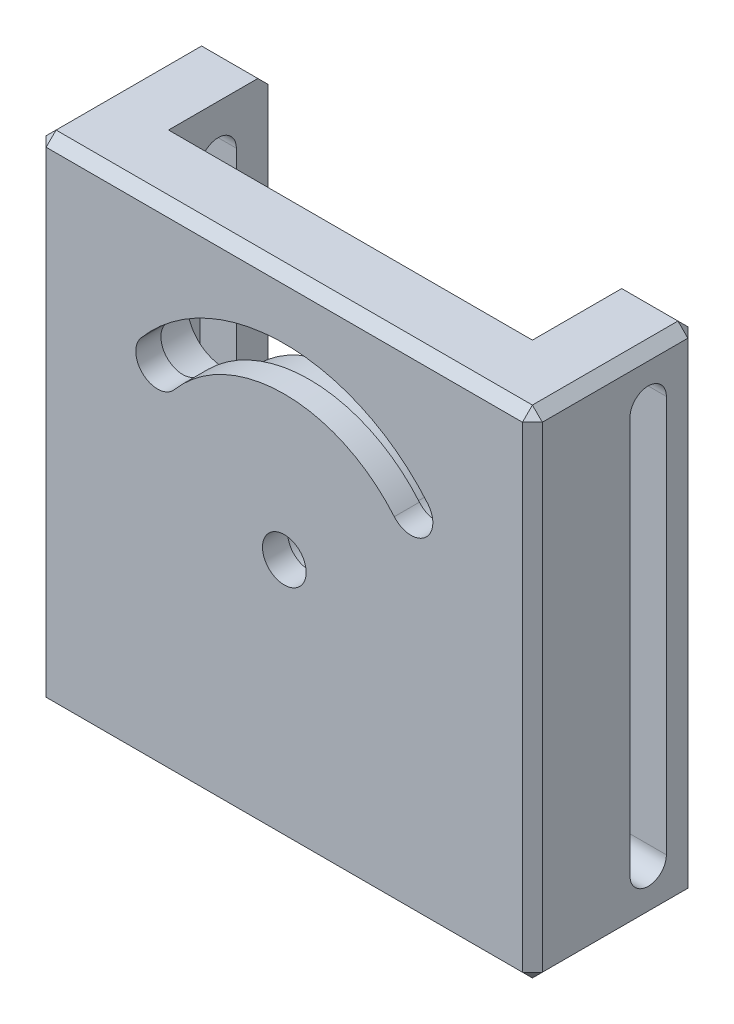
SolidWorks part; units mm, degrees
material "Alumina"
ref_plane "Front Plane" through (0, 0, 0) normal (0, 0, 1) x (1, 0, 0)
ref_plane "Top Plane" through (0, 0, 0) normal (0, 1, 0) x (1, 0, 0)
ref_plane "Right Plane" through (0, 0, 0) normal (1, 0, 0) x (0, 0, -1)
sketch "Sketch1" plane through (0, 0, 0) normal (0, 0, 1) x (1, 0, 0)
  line L1 (-32.5, 37.5) -> (32.5, 37.5)
  line L2 (-32.5, 37.5) -> (-32.5, -37.5)
  line L3 (-32.5, -37.5) -> (32.5, -37.5)
  line L4 (32.5, 37.5) -> (32.5, -37.5)
  line L5 (-32.5, 37.5) -> (32.5, -37.5) construction
  line L6 (-32.5, -37.5) -> (32.5, 37.5) construction
  point P0 (0, 0)
  dimension "D1" = 65
  dimension "D2" = 75
extrude "Boss-Extrude1" add sketch "Sketch1" along normal blind 10
sketch "Sketch2" plane through (0, 0, 0) normal (0, 0, -1) x (-1, 0, 0)
  line L0 (32.5, -37.5) -> (-32.5, -37.5) construction
  line L1 (-32.5, 37.5) -> (-27.5, 37.5)
  line L2 (-32.5, 37.5) -> (-32.5, -37.5)
  line L3 (-32.5, -37.5) -> (-27.5, -37.5)
  line L4 (-27.5, 37.5) -> (-27.5, -37.5)
  line L6 (32.5, 37.5) -> (27.5, 37.5)
  line L7 (32.5, 37.5) -> (32.5, -37.5)
  line L8 (32.5, -37.5) -> (27.5, -37.5)
  line L9 (27.5, 37.5) -> (27.5, -37.5)
  dimension "D1" = 5
  dimension "D2" = 5
extrude "Boss-Extrude2" add sketch "Sketch2" along normal blind 15
sketch "Sketch3" plane through (-32.5, 0, 0) normal (-1, 0, 0) x (0, 0, 1)
  line L0 (-7.5, 30) -> (-7.5, -30) construction
  line L1 (-4.75, 30) -> (-4.75, -30)
  line L2 (-10.25, 30) -> (-10.25, -30)
  line L3 (10, -37.5) -> (-15, -37.5) construction
  line L4 (10, 37.5) -> (-15, 37.5) construction
  line L5 (-15, -37.5) -> (-15, 37.5) construction
  arc A0 (-4.75, 30) -> (-10.25, 30) centre (-7.5, 30) ccw
  arc A1 (-10.25, -30) -> (-4.75, -30) centre (-7.5, -30) ccw
  point P2 (-7.5, 0)
  dimension "D1" = 7.5
  dimension "D2" = 7.5
  dimension "D3" = 7.5
extrude "Cut-Extrude1" cut sketch "Sketch3" against normal blind 109
sketch "Sketch4" plane through (0, 0, 0) normal (0, 0, -1) x (-1, 0, 0)
  arc A4 (-23.3644, 19.605) -> (-14.9379, 12.5344) centre (-19.1511, 16.0697) ccw
  arc A5 (14.9379, 12.5344) -> (23.3644, 19.605) centre (19.1511, 16.0697) ccw
  arc A6 (14.9379, 12.5344) -> (-14.9379, 12.5344) centre (0, 0) ccw
  arc A7 (23.3644, 19.605) -> (-23.3644, 19.605) centre (0, 0) ccw
extrude "Cut-Extrude3" cut sketch "Sketch4" against normal blind 6.2
sketch "Sketch5" plane through (0, 0, 0) normal (0, 0, -1) x (-1, 0, 0)
  arc A0 (-21.6791, 18.1909) -> (-16.6232, 13.9485) centre (-19.1511, 16.0697) ccw
  arc A1 (16.6232, 13.9485) -> (21.6791, 18.1909) centre (19.1511, 16.0697) ccw
  arc A2 (16.6232, 13.9485) -> (-16.6232, 13.9485) centre (0, 0) ccw
  arc A3 (21.6791, 18.1909) -> (-21.6791, 18.1909) centre (0, 0) ccw
extrude "Cut-Extrude4" cut sketch "Sketch5" against normal blind 48.4
hole_wizard "CBORE for M6 Hex Socket Head Cap Screw1" positions "Sketch6" profile "Sketch7" counterbore size "M6" standard "DIN" end condition through all
sketch "Sketch6" plane through (0, 0, 0) normal (0, 0, -1) x (-1, 0, 0)
  point P0 (0, 0)
sketch "Sketch7" plane through (0, 0, 0) normal (1, 0, 0) x (0, 1, 0)
  line L0 (0, 0) -> (0, 10)
  line L1 (0, 10) -> (3.3, 10)
  line L3 (3.3, 10) -> (3.3, 6.2)
  line L4 (3.3, 6.2) -> (5.5, 6.2)
  line L5 (5.5, 6.2) -> (5.5, 0)
  line L7 (5.5, 0) -> (0, 0)
  line L11 (0, -6.35) -> (0, 107.95) construction
  dimension "Thru Hole Dia." = 6.6
  dimension "Thru Hole Depth" = 10
  dimension "C'Bore Dia." = 11
  dimension "C'Bore Depth" = 6.2
sketch "Sketch8" plane through (-32.5, 0, 0) normal (-1, 0, 0) x (0, 0, 1)
  line L0 (-7.5, 30) -> (-7.5, -30) construction
  line L1 (-1.1969, 30) -> (-1.1969, -30)
  line L2 (-13.8031, 30) -> (-13.8031, -30)
  arc A0 (-1.1969, 30) -> (-13.8031, 30) centre (-7.5, 30) ccw
  arc A1 (-13.8031, -30) -> (-1.1969, -30) centre (-7.5, -30) ccw
  point P4 (-7.5, 0)
sketch "Sketch9" plane through (-32.5, 0, 0) normal (-1, 0, 0) x (0, 0, 1)
  line L0 (-7.5, 30) -> (-7.5, -30) construction
  line L1 (-15, 37.5) -> (10, 37.5)
  line L2 (-15, 37.5) -> (-15, -37.5)
  line L3 (-15, -37.5) -> (10, -37.5)
  line L4 (10, 37.5) -> (10, -37.5)
  line L5 (-4.75, 30) -> (-4.75, -30)
  line L6 (-10.25, 30) -> (-10.25, -30)
  arc A0 (-4.75, 30) -> (-10.25, 30) centre (-7.5, 30) ccw
  arc A1 (-10.25, -30) -> (-4.75, -30) centre (-7.5, -30) ccw
  point P10 (-7.5, 0)
extrude "Boss-Extrude3" add sketch "Sketch9" along normal blind 5
ref_plane "Plane1" through (0, 0, 0) normal (-1, 0, 0) x (0, 0, 1)
mirror "Mirror1" about plane through (0, 0, 0) normal (-1, 0, 0) of "Boss-Extrude3"
chamfer "Chamfer1" distance 1.5 angle 45 14 edges at (32.5, 37.5, -15) (37.5, 0, -15) (37.5, 0, 10) (32.5, -37.5, -15) (-32.5, -37.5, -15) (-37.5, 0, -15) (-32.5, 37.5, -15) (37.5, 37.5, -2.5) (37.5, -37.5, -2.5) (0, -37.5, 10) (-37.5, -37.5, -2.5) (-37.5, 0, 10) (-37.5, 37.5, -2.5) (0, 37.5, 10)
